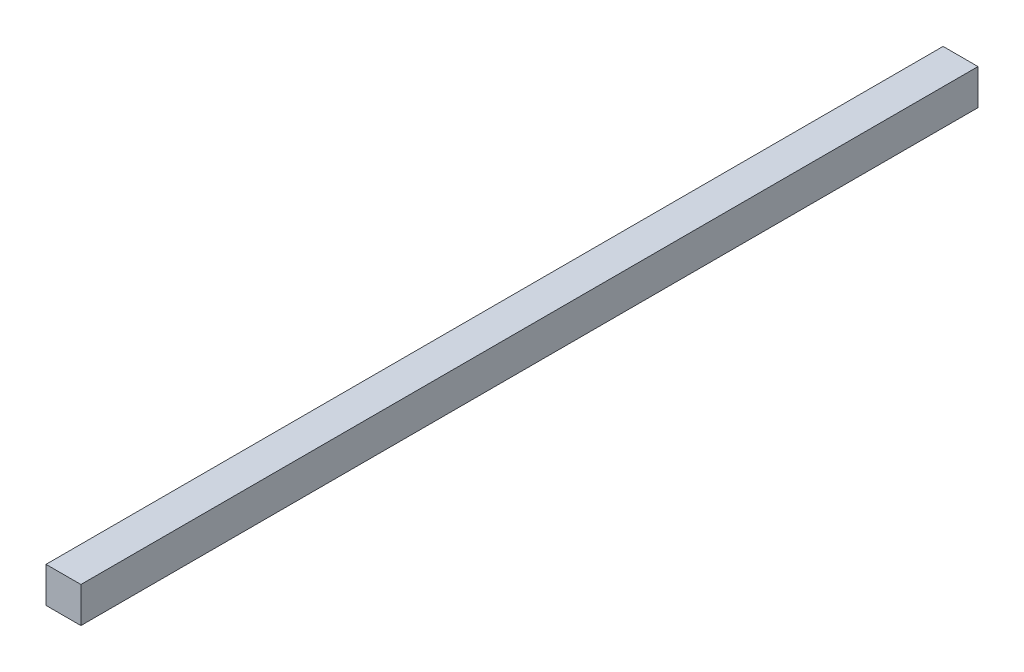
SolidWorks part; units mm, degrees
ref_plane "前视基准面" through (0, 0, 0) normal (0, 0, 1) x (1, 0, 0)
ref_plane "上视基准面" through (0, 0, 0) normal (0, 1, 0) x (1, 0, 0)
ref_plane "右视基准面" through (0, 0, 0) normal (1, 0, 0) x (0, 0, -1)
other "Configuration Table"
sketch "草图1" plane through (0, 0, 0) normal (0, 0, 1) x (1, 0, 0)
  line L1 (-5.8369, -5.9535) -> (5.8369, -5.9535)
  line L2 (-5.8369, -5.9535) -> (-5.8369, 5.9535)
  line L3 (-5.8369, 5.9535) -> (5.8369, 5.9535)
  line L4 (5.8369, -5.9535) -> (5.8369, 5.9535)
  line L5 (-5.8369, -5.9535) -> (5.8369, 5.9535) construction
  line L6 (-5.8369, 5.9535) -> (5.8369, -5.9535) construction
  point P0 (0, 0)
extrude "凸台-拉伸1" add sketch "草图1" along normal blind 300
